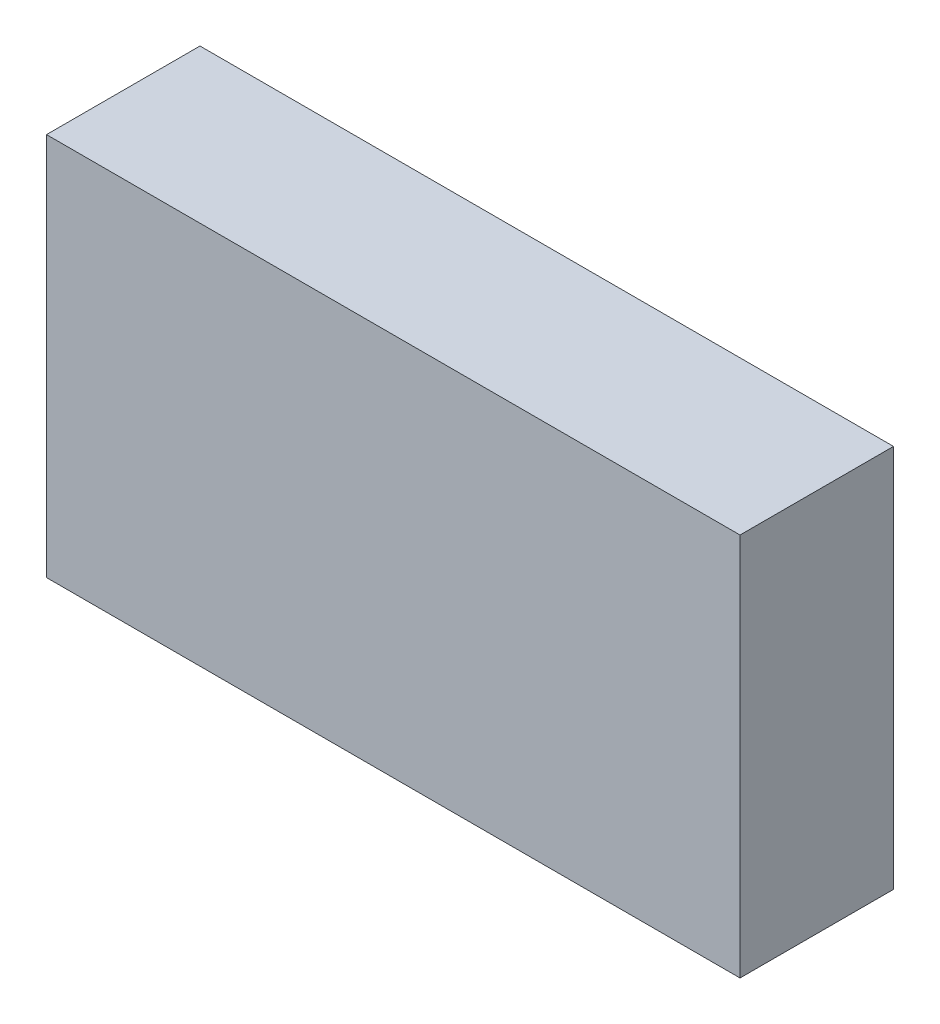
SolidWorks part; units mm, degrees
ref_plane "Front Plane" through (0, 0, 0) normal (0, 0, 1) x (1, 0, 0)
ref_plane "Top Plane" through (0, 0, 0) normal (0, 1, 0) x (1, 0, 0)
ref_plane "Right Plane" through (0, 0, 0) normal (1, 0, 0) x (0, 0, -1)
sketch "Sketch1" plane through (0, 0, 0) normal (0, 0, 1) x (1, 0, 0)
  line L1 (-117.5, -65) -> (117.5, -65)
  line L2 (-117.5, -65) -> (-117.5, 65)
  line L3 (-117.5, 65) -> (117.5, 65)
  line L4 (117.5, -65) -> (117.5, 65)
  line L5 (-117.5, -65) -> (117.5, 65) construction
  line L6 (-117.5, 65) -> (117.5, -65) construction
  point P0 (0, 0)
  dimension "D1" = 235
  dimension "D2" = 130
extrude "Boss-Extrude1" add sketch "Sketch1" along normal mid plane 52
